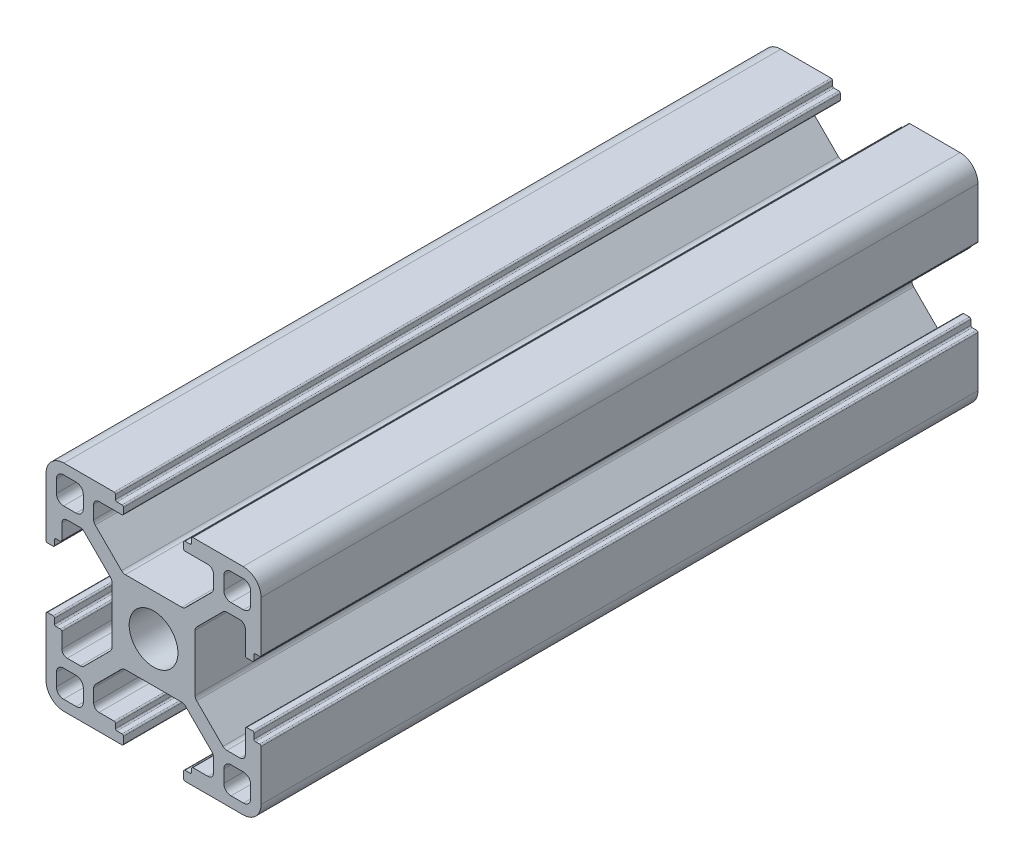
SolidWorks part; units mm, degrees
material "6063-T5"
ref_plane "Front Plane" through (0, 0, 0) normal (0, 0, 1) x (1, 0, 0)
ref_plane "Top Plane" through (0, 0, 0) normal (0, 1, 0) x (1, 0, 0)
ref_plane "Right Plane" through (0, 0, 0) normal (1, 0, 0) x (0, 0, -1)
sketch "Sketch1" plane through (0, 0, 0) normal (0, 0, 1) x (1, 0, 0)
  line L0 (0, 2.5) -> (0, 10.6)
  line L1 (2.5, 30) -> (9.5, 30)
  line L2 (30, 27.5) -> (30, 20.5)
  line L3 (27.5, 0) -> (19.4, 0)
  line L4 (19.464, 9.1128) -> (23.1303, 5.4465)
  line L5 (21.0197, 10.536) -> (24.686, 6.8697)
  line L6 (10.536, 21.0197) -> (6.8697, 24.686)
  line L7 (8.9803, 19.464) -> (5.314, 23.1303)
  line L8 (11.0663, 20.8) -> (18.9337, 20.8)
  line L9 (20.8, 18.9337) -> (20.8, 11.0663)
  line L10 (18.9337, 9.3324) -> (11.0663, 9.3324)
  line L11 (9.2, 11.0663) -> (9.2, 18.9337)
  line L12 (0, 19.4) -> (0, 27.5)
  line L13 (30, 9.5) -> (30, 2.5)
  line L14 (19.4, 27.8) -> (22.6, 27.8)
  line L15 (10.6, 27.8) -> (7.4, 27.8)
  line L16 (10.6, 0) -> (2.5, 0)
  line L17 (2.2, 20.5) -> (2.2, 22.6)
  line L18 (2.2, 9.5) -> (2.2, 7.4)
  line L19 (9.5, 2.3324) -> (7.4, 2.3324)
  line L20 (19.464, 21.0197) -> (23.1303, 24.686)
  line L21 (21.0197, 19.464) -> (24.686, 23.1303)
  line L22 (8.9803, 10.536) -> (5.314, 6.8697)
  line L23 (10.536, 9.1128) -> (6.8697, 5.4465)
  line L24 (10.8, 28.8) -> (10.8, 28)
  line L25 (19.2, 28.8) -> (19.2, 28)
  line L26 (0.2, 19.2) -> (1, 19.2)
  line L27 (0.2, 10.8) -> (1, 10.8)
  line L28 (28.8, 19.2) -> (28, 19.2)
  line L29 (28.8, 10.8) -> (28, 10.8)
  line L30 (10.8, 0.2) -> (10.8, 1.1324)
  line L31 (19.2, 0.2) -> (19.2, 1.1324)
  line L32 (20.5, 30) -> (27.5, 30)
  line L33 (27.8, 19.4) -> (27.8, 22.6)
  line L34 (27.8, 10.6) -> (27.8, 7.4)
  line L35 (20.5, 2.2) -> (22.6, 2.2)
  line L36 (6.65, 27.05) -> (6.65, 25.2163)
  line L37 (23.35, 27.05) -> (23.35, 25.2163)
  line L38 (2.95, 23.35) -> (4.7837, 23.35)
  line L39 (27.05, 23.35) -> (25.2163, 23.35)
  line L40 (2.95, 6.65) -> (4.7837, 6.65)
  line L41 (6.65, 3.0824) -> (6.65, 4.9161)
  line L42 (23.35, 2.95) -> (23.35, 4.9161)
  line L43 (27.05, 6.65) -> (25.2163, 6.65)
  line L44 (29, 10.6) -> (29, 9.9)
  line L45 (29.8, 20.3) -> (29.2, 20.3)
  line L46 (29, 20.1) -> (29, 19.4)
  line L47 (29.2, 9.7) -> (29.8, 9.7)
  line L48 (19.4, 29) -> (20.1, 29)
  line L49 (9.7, 29.8) -> (9.7, 29.2)
  line L50 (9.9, 29) -> (10.6, 29)
  line L51 (20.3, 29.2) -> (20.3, 29.8)
  line L52 (9.7, 2.1324) -> (9.7, 1.5324)
  line L53 (9.9, 1.3324) -> (10.6, 1.3324)
  line L54 (19.4, 1.3324) -> (20.1, 1.3324)
  line L55 (20.3, 1.5324) -> (20.3, 2)
  line L56 (2, 20.3) -> (1.4, 20.3)
  line L57 (1.2, 20.1) -> (1.2, 19.4)
  line L58 (1.2, 10.6) -> (1.2, 9.9)
  line L59 (1.4, 9.7) -> (2, 9.7)
  line L60 (27.55, 1.45) -> (25.8, 1.45)
  line L61 (24.8, 2.45) -> (24.8, 4.2)
  line L62 (25.8, 5.2) -> (27.55, 5.2)
  line L63 (28.55, 4.2) -> (28.55, 2.45)
  line L64 (24.8, 25.8) -> (24.8, 27.55)
  line L65 (25.8, 28.55) -> (27.55, 28.55)
  line L66 (28.55, 27.55) -> (28.55, 25.8)
  line L67 (27.55, 24.8) -> (25.8, 24.8)
  line L68 (2.45, 28.55) -> (4.2, 28.55)
  line L69 (5.2, 27.55) -> (5.2, 25.8)
  line L70 (1.45, 2.45) -> (1.45, 4.2)
  line L71 (2.45, 5.2) -> (4.2, 5.2)
  line L72 (5.2, 4.2) -> (5.2, 2.45)
  line L73 (4.2, 1.45) -> (2.45, 1.45)
  line L74 (4.2, 24.8) -> (2.45, 24.8)
  line L75 (1.45, 25.8) -> (1.45, 27.55)
  circle A0 centre (15, 15) radius 3.4
  arc A1 (25.8, 1.45) -> (24.8, 2.45) centre (25.8, 2.45) cw
  arc A2 (27.55, 1.45) -> (28.55, 2.45) centre (27.55, 2.45) ccw
  arc A3 (27.55, 5.2) -> (28.55, 4.2) centre (27.55, 4.2) cw
  arc A4 (24.8, 4.2) -> (25.8, 5.2) centre (25.8, 4.2) cw
  arc A5 (1.45, 2.45) -> (2.45, 1.45) centre (2.45, 2.45) ccw
  arc A6 (5.2, 2.45) -> (4.2, 1.45) centre (4.2, 2.45) cw
  arc A7 (4.2, 5.2) -> (5.2, 4.2) centre (4.2, 4.2) cw
  arc A8 (1.45, 4.2) -> (2.45, 5.2) centre (2.45, 4.2) cw
  arc A9 (24.8, 25.8) -> (25.8, 24.8) centre (25.8, 25.8) ccw
  arc A10 (28.55, 25.8) -> (27.55, 24.8) centre (27.55, 25.8) cw
  arc A11 (27.55, 28.55) -> (28.55, 27.55) centre (27.55, 27.55) cw
  arc A12 (24.8, 27.55) -> (25.8, 28.55) centre (25.8, 27.55) cw
  arc A13 (4.2, 28.55) -> (5.2, 27.55) centre (4.2, 27.55) cw
  arc A14 (5.2, 25.8) -> (4.2, 24.8) centre (4.2, 25.8) cw
  arc A15 (2.45, 24.8) -> (1.45, 25.8) centre (2.45, 25.8) cw
  arc A16 (2.45, 28.55) -> (1.45, 27.55) centre (2.45, 27.55) ccw
  arc A17 (30, 2.5) -> (27.5, 0) centre (27.5, 2.5) cw
  arc A18 (0, 2.5) -> (2.5, 0) centre (2.5, 2.5) ccw
  arc A19 (27.5, 30) -> (30, 27.5) centre (27.5, 27.5) cw
  arc A20 (0, 27.5) -> (2.5, 30) centre (2.5, 27.5) cw
  arc A21 (0, 10.6) -> (0.2, 10.8) centre (0.2, 10.6) cw
  arc A22 (1.2, 10.6) -> (1, 10.8) centre (1, 10.6) ccw
  arc A23 (2, 9.7) -> (2.2, 9.5) centre (2, 9.5) cw
  arc A24 (9.7, 2.1324) -> (9.5, 2.3324) centre (9.5, 2.1324) ccw
  arc A25 (10.6, 1.3324) -> (10.8, 1.1324) centre (10.6, 1.1324) cw
  arc A26 (10.6, 0) -> (10.8, 0.2) centre (10.6, 0.2) ccw
  arc A27 (19.4, 0) -> (19.2, 0.2) centre (19.4, 0.2) cw
  arc A28 (19.4, 1.3324) -> (19.2, 1.1324) centre (19.4, 1.1324) ccw
  arc A29 (20.3, 2) -> (20.5, 2.2) centre (20.5, 2) cw
  arc A30 (28, 10.8) -> (27.8, 10.6) centre (28, 10.6) ccw
  arc A31 (29, 10.6) -> (28.8, 10.8) centre (28.8, 10.6) ccw
  arc A32 (29.8, 9.7) -> (30, 9.5) centre (29.8, 9.5) cw
  arc A33 (28, 19.2) -> (27.8, 19.4) centre (28, 19.4) cw
  arc A34 (29, 19.4) -> (28.8, 19.2) centre (28.8, 19.4) cw
  arc A35 (30, 20.5) -> (29.8, 20.3) centre (29.8, 20.5) cw
  arc A36 (20.3, 29.8) -> (20.5, 30) centre (20.5, 29.8) cw
  arc A37 (19.4, 29) -> (19.2, 28.8) centre (19.4, 28.8) ccw
  arc A38 (19.2, 28) -> (19.4, 27.8) centre (19.4, 28) ccw
  arc A39 (10.8, 28) -> (10.6, 27.8) centre (10.6, 28) cw
  arc A40 (0, 19.4) -> (0.2, 19.2) centre (0.2, 19.4) ccw
  arc A41 (1.2, 19.4) -> (1, 19.2) centre (1, 19.4) cw
  arc A42 (2, 20.3) -> (2.2, 20.5) centre (2, 20.5) ccw
  arc A43 (10.6, 29) -> (10.8, 28.8) centre (10.6, 28.8) cw
  arc A44 (9.5, 30) -> (9.7, 29.8) centre (9.5, 29.8) cw
  arc A45 (1.4, 20.3) -> (1.2, 20.1) centre (1.4, 20.1) ccw
  arc A46 (20.1, 29) -> (20.3, 29.2) centre (20.1, 29.2) ccw
  arc A47 (9.7, 29.2) -> (9.9, 29) centre (9.9, 29.2) ccw
  arc A48 (29.2, 20.3) -> (29, 20.1) centre (29.2, 20.1) ccw
  arc A49 (29, 9.9) -> (29.2, 9.7) centre (29.2, 9.9) ccw
  arc A50 (20.1, 1.3324) -> (20.3, 1.5324) centre (20.1, 1.5324) ccw
  arc A51 (1.2, 9.9) -> (1.4, 9.7) centre (1.4, 9.9) ccw
  arc A52 (9.7, 1.5324) -> (9.9, 1.3324) centre (9.9, 1.5324) ccw
  arc A53 (23.35, 25.2163) -> (23.1303, 24.686) centre (22.6, 25.2163) cw
  arc A54 (25.2163, 23.35) -> (24.686, 23.1303) centre (25.2163, 22.6) ccw
  arc A55 (20.8, 18.9337) -> (21.0197, 19.464) centre (21.55, 18.9337) cw
  arc A56 (18.9337, 20.8) -> (19.464, 21.0197) centre (18.9337, 21.55) ccw
  arc A57 (6.65, 25.2163) -> (6.8697, 24.686) centre (7.4, 25.2163) ccw
  arc A58 (11.0663, 20.8) -> (10.536, 21.0197) centre (11.0663, 21.55) cw
  arc A59 (4.7837, 23.35) -> (5.314, 23.1303) centre (4.7837, 22.6) cw
  arc A60 (9.2, 18.9337) -> (8.9803, 19.464) centre (8.45, 18.9337) ccw
  arc A61 (4.7837, 6.65) -> (5.314, 6.8697) centre (4.7837, 7.4) ccw
  arc A62 (9.2, 11.0663) -> (8.9803, 10.536) centre (8.45, 11.0663) cw
  arc A63 (6.65, 4.9161) -> (6.8697, 5.4465) centre (7.4, 4.9161) cw
  arc A64 (11.0663, 9.3324) -> (10.536, 9.1128) centre (11.0663, 8.5824) ccw
  arc A65 (18.9337, 9.3324) -> (19.464, 9.1128) centre (18.9337, 8.5824) cw
  arc A66 (20.8, 11.0663) -> (21.0197, 10.536) centre (21.55, 11.0663) ccw
  arc A67 (25.2163, 6.65) -> (24.686, 6.8697) centre (25.2163, 7.4) cw
  arc A68 (23.35, 4.9161) -> (23.1303, 5.4465) centre (22.6, 4.9161) ccw
  arc A69 (7.4, 2.3324) -> (6.65, 3.0824) centre (7.4, 3.0824) cw
  arc A70 (22.6, 2.2) -> (23.35, 2.95) centre (22.6, 2.95) ccw
  arc A71 (27.8, 7.4) -> (27.05, 6.65) centre (27.05, 7.4) cw
  arc A72 (27.8, 22.6) -> (27.05, 23.35) centre (27.05, 22.6) ccw
  arc A73 (22.6, 27.8) -> (23.35, 27.05) centre (22.6, 27.05) cw
  arc A74 (2.2, 7.4) -> (2.95, 6.65) centre (2.95, 7.4) ccw
  arc A75 (2.2, 22.6) -> (2.95, 23.35) centre (2.95, 22.6) cw
  arc A76 (7.4, 27.8) -> (6.65, 27.05) centre (7.4, 27.05) ccw
  point P115 (0, 0)
extrude "Boss-Extrude1" add sketch "Sketch1" along normal blind 100
